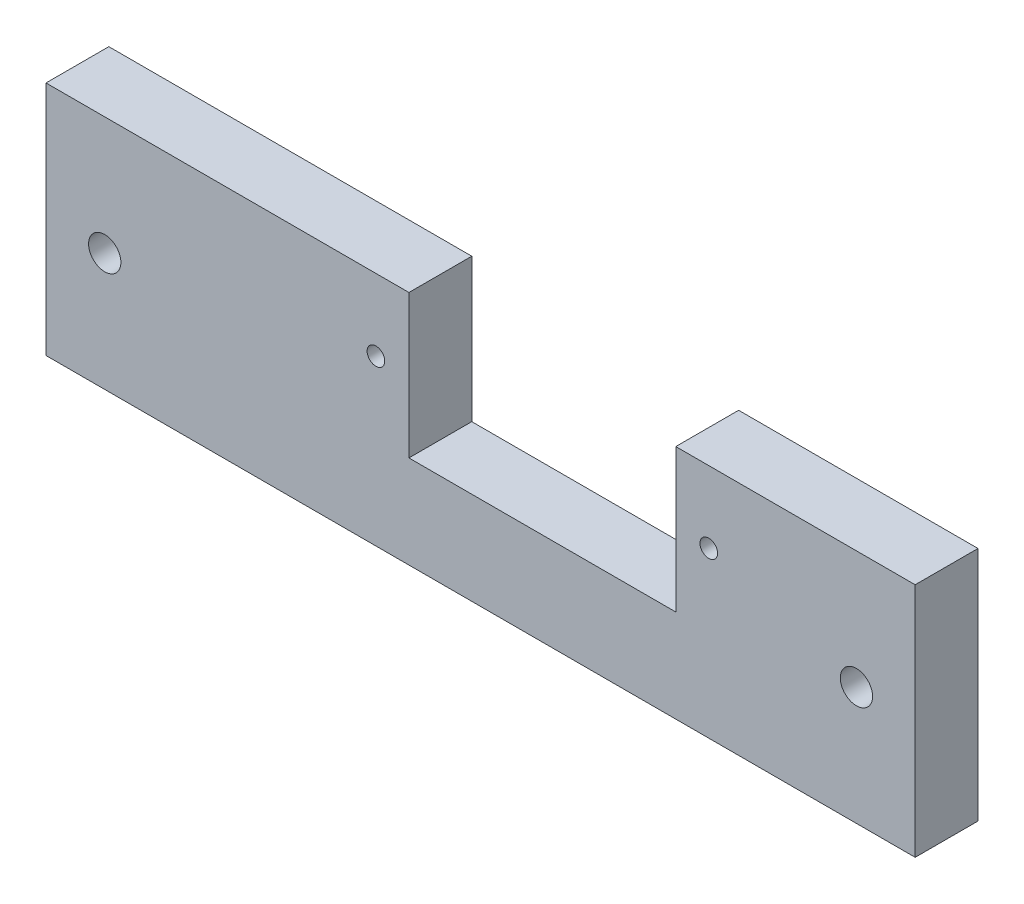
SolidWorks part; units mm, degrees
ref_plane "Front Plane" through (0, 0, 0) normal (0, 0, 1) x (1, 0, 0)
ref_plane "Top Plane" through (0, 0, 0) normal (0, 1, 0) x (1, 0, 0)
ref_plane "Right Plane" through (0, 0, 0) normal (1, 0, 0) x (0, 0, -1)
sketch "Model" plane through (0, 0, 0) normal (0, 0, 1) x (1, 0, 0)
  line L0 (0, 10.05) -> (74, 10.05) construction
  line L1 (0, 0) -> (74, 0)
  line L2 (0, 0) -> (0, 20.1)
  line L3 (0, 20.1) -> (30.9, 20.1)
  line L4 (74, 0) -> (74, 20.1)
  line L5 (42.26, 7.9) -> (42.26, 28.0438) construction
  line L6 (30.9, 20.1) -> (30.9, 7.9)
  line L7 (30.9, 7.9) -> (53.62, 7.9)
  line L8 (53.62, 20.1) -> (53.62, 7.9)
  line L9 (37, 0) -> (37, 20.1) construction
  line L10 (53.62, 20.1) -> (74, 20.1)
  circle A0 centre (5, 10.05) radius 1.2
  circle A1 centre (28.09, 14) radius 0.75
  circle A2 centre (56.43, 14) radius 0.75
  circle A3 centre (69, 10.05) radius 1.375
  circle A4 centre (5, 10.05) radius 1.375
  circle A5 centre (69, 10.05) radius 1.2
  point P17 (5, 10.05)
  dimension "D4" = 2.4
  dimension "D6" = 0.175
  dimension "D9" = 5
  dimension "D23" = 1.5
  dimension "D25" = 2.81
  dimension "D27" = 6.1
  dimension "D2" = 74
  dimension "D8" = 20.1
  dimension "D16" = 22.72
  dimension "D18" = 30.9
  dimension "D20" = 12.2
extrude "Boss-Extrude1" add sketch "Model" along normal blind 5.35 contours L10 L8 L7 L6 L3 L2 L1 L4 A4 A2 A1 A3
equation "\"mdfthick\"=5.35"
equation "\"D1@Boss-Extrude1\"=\"mdfthick\""
